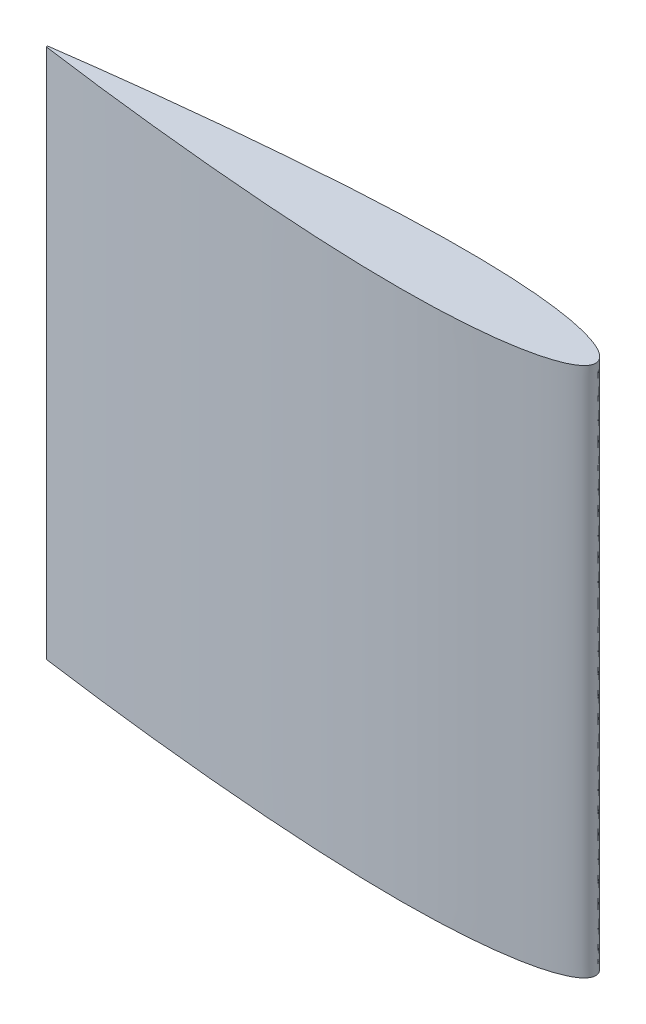
SolidWorks part; units mm, degrees
ref_plane "Front Plane" through (0, 0, 0) normal (0, 0, 1) x (1, 0, 0)
ref_plane "Top Plane" through (0, 0, 0) normal (0, 1, 0) x (1, 0, 0)
ref_plane "Right Plane" through (0, 0, 0) normal (1, 0, 0) x (0, 0, -1)
other "Center of Mass"
curve "Curve1"
  spline degree 3 poles (1, 0.0013, 0) (0.9998, 0.0013, 0) (0.999, 0.0014, 0) (0.9973, 0.0016, 0) (0.9944, 0.002, 0) (0.9903, 0.0026, 0) (0.9851, 0.0033, 0) (0.9788, 0.0042, 0) (0.9713, 0.0052, 0) (0.9627, 0.0064, 0) (0.9531, 0.0077, 0) (0.9424, 0.0091, 0) (0.9307, 0.0106, 0) (0.9179, 0.0122, 0) (0.9042, 0.014, 0) (0.8895, 0.0158, 0) (0.874, 0.0177, 0) (0.8575, 0.0196, 0) (0.8402, 0.0217, 0) (0.8222, 0.0237, 0) (0.8033, 0.0259, 0) (0.7838, 0.028, 0) (0.7636, 0.0302, 0) (0.7428, 0.0324, 0) (0.7214, 0.0345, 0) (0.6995, 0.0367, 0) (0.6772, 0.0388, 0) (0.6544, 0.0409, 0) (0.6313, 0.043, 0) (0.6078, 0.045, 0) (0.5841, 0.0469, 0) (0.5602, 0.0488, 0) (0.5362, 0.0505, 0) (0.5121, 0.0522, 0) (0.4879, 0.0537, 0) (0.4638, 0.0551, 0) (0.4398, 0.0563, 0) (0.4159, 0.0574, 0) (0.3922, 0.0583, 0) (0.3688, 0.0591, 0) (0.3456, 0.0596, 0) (0.3228, 0.0599, 0) (0.3005, 0.0601, 0) (0.2786, 0.06, 0) (0.2572, 0.0596, 0) (0.2364, 0.0591, 0) (0.2162, 0.0583, 0) (0.1966, 0.0572, 0) (0.1778, 0.056, 0) (0.1597, 0.0544, 0) (0.1425, 0.0527, 0) (0.126, 0.0507, 0) (0.1104, 0.0486, 0) (0.0958, 0.0462, 0) (0.0821, 0.0436, 0) (0.0693, 0.0408, 0) (0.0576, 0.0378, 0) (0.0468, 0.0347, 0) (0.0372, 0.0313, 0) (0.0286, 0.0279, 0) (0.0211, 0.0243, 0) (0.0147, 0.0206, 0) (0.0094, 0.0167, 0) (0.0053, 0.0128, 0) (0.0023, 0.0087, 0) (0.0004, 0.0044, 0) (-0.0002, 0, 0) (0.0004, -0.0044, 0) (0.0023, -0.0087, 0) (0.0053, -0.0128, 0) (0.0094, -0.0167, 0) (0.0147, -0.0206, 0) (0.0211, -0.0243, 0) (0.0286, -0.0279, 0) (0.0372, -0.0313, 0) (0.0468, -0.0347, 0) (0.0576, -0.0378, 0) (0.0693, -0.0408, 0) (0.0821, -0.0436, 0) (0.0958, -0.0462, 0) (0.1104, -0.0486, 0) (0.126, -0.0507, 0) (0.1425, -0.0527, 0) (0.1597, -0.0544, 0) (0.1778, -0.056, 0) (0.1966, -0.0572, 0) (0.2162, -0.0583, 0) (0.2364, -0.0591, 0) (0.2572, -0.0596, 0) (0.2786, -0.06, 0) (0.3005, -0.0601, 0) (0.3228, -0.0599, 0) (0.3456, -0.0596, 0) (0.3688, -0.0591, 0) (0.3922, -0.0583, 0) (0.4159, -0.0574, 0) (0.4398, -0.0563, 0) (0.4638, -0.0551, 0) (0.4879, -0.0537, 0) (0.5121, -0.0522, 0) (0.5362, -0.0505, 0) (0.5602, -0.0488, 0) (0.5841, -0.0469, 0) (0.6078, -0.045, 0) (0.6313, -0.043, 0) (0.6544, -0.0409, 0) (0.6772, -0.0388, 0) (0.6995, -0.0367, 0) (0.7214, -0.0345, 0) (0.7428, -0.0324, 0) (0.7636, -0.0302, 0) (0.7838, -0.028, 0) (0.8033, -0.0259, 0) (0.8222, -0.0237, 0) (0.8402, -0.0217, 0) (0.8575, -0.0196, 0) (0.874, -0.0177, 0) (0.8895, -0.0158, 0) (0.9042, -0.014, 0) (0.9179, -0.0122, 0) (0.9307, -0.0106, 0) (0.9424, -0.0091, 0) (0.9531, -0.0077, 0) (0.9627, -0.0064, 0) (0.9713, -0.0052, 0) (0.9788, -0.0042, 0) (0.9851, -0.0033, 0) (0.9903, -0.0026, 0) (0.9944, -0.002, 0) (0.9973, -0.0016, 0) (0.999, -0.0014, 0) (0.9998, -0.0013, 0) (1, -0.0013, 0) knots 0 0 0 0 0.000289 0.001156 0.002598 0.004612 0.007194 0.010336 0.014031 0.018272 0.023046 0.028343 0.03415 0.040454 0.047238 0.054489 0.062187 0.070314 0.078852 0.08778 0.097078 0.106722 0.116691 0.126961 0.137507 0.148306 0.159331 0.170556 0.181957 0.193504 0.205171 0.216932 0.228758 0.240621 0.252495 0.26435 0.276161 0.287898 0.299536 0.311047 0.322405 0.333584 0.344559 0.355306 0.3658 0.376018 0.385937 0.395538 0.404798 0.413699 0.422221 0.430349 0.438066 0.445357 0.452209 0.458612 0.464554 0.47003 0.475035 0.479569 0.483637 0.48725 0.490431 0.493219 0.495674 0.497891 0.5 0.502109 0.504326 0.506781 0.509569 0.51275 0.516363 0.520431 0.524965 0.52997 0.535446 0.541388 0.547791 0.554643 0.561934 0.569651 0.577779 0.586301 0.595202 0.604462 0.614063 0.623982 0.6342 0.644694 0.655441 0.666416 0.677595 0.688953 0.700464 0.712102 0.723839 0.73565 0.747505 0.759379 0.771242 0.783068 0.794829 0.806496 0.818043 0.829444 0.840669 0.851694 0.862493 0.873039 0.883309 0.893278 0.902922 0.91222 0.921148 0.929686 0.937813 0.945511 0.952762 0.959546 0.96585 0.971657 0.976954 0.981728 0.985969 0.989664 0.992806 0.995388 0.997402 0.998844 0.999711 1 1 1 1
sketch "Sketch3" plane through (0, 0, 0) normal (0, 1, 0) x (1, 0, 0)
  line L0 (-600, 0.811) -> (-600, 1.189)
  line L1 (-450, 1) -> (-600, 1) construction
  line L2 (-450, 1) -> (-450, -67.7487) construction
  spline S0 degree 3 poles (-600, 0.811) (-597.1383, 0.409) (-586.3551, -1.0487) (-571.3391, -2.8356) (-553.4048, -4.6847) (-539.8063, -5.8991) (-526.805, -6.8522) (-516.0279, -7.4788) (-505.4381, -7.8939) (-495.2572, -8.0517) (-486.6423, -7.9301) (-479.5995, -7.6106) (-474.0744, -7.2001) (-469.0237, -6.6516) (-465.1394, -6.0705) (-462.3078, -5.5341) (-460.3955, -5.1154) (-458.6338, -4.6692) (-457.0267, -4.1976) (-455.5775, -3.7022) (-454.2895, -3.1846) (-453.1652, -2.6464) (-452.2067, -2.0886) (-451.4151, -1.5123) (-450.792, -0.9164) (-450.3389, -0.2993) (-450.0619, 0.342) (-449.9698, 1) (-450.0619, 1.658) (-450.3389, 2.2993) (-450.792, 2.9164) (-451.4151, 3.5123) (-452.2067, 4.0886) (-453.1652, 4.6464) (-454.2895, 5.1846) (-455.5775, 5.7022) (-457.0267, 6.1976) (-458.6338, 6.6692) (-460.3955, 7.1154) (-463.0341, 7.6932) (-466.6909, 8.3286) (-471.4868, 8.9425) (-477.7882, 9.5143) (-485.6982, 9.9164) (-496.4309, 10.0682) (-507.8157, 9.8328) (-519.6106, 9.2909) (-530.4, 8.605) (-542.1964, 7.6892) (-552.5331, 6.7493) (-565.8552, 5.4137) (-579.0317, 3.9401) (-591.6106, 2.3422) (-597.8927, 1.484) (-599.7377, 1.2258) (-600, 1.189) knots 0 0 0 0 0.028343 0.106722 0.148306 0.205171 0.240621 0.276161 0.311047 0.344559 0.376018 0.395538 0.413699 0.430349 0.445357 0.452209 0.458612 0.464554 0.47003 0.475035 0.479569 0.483637 0.48725 0.490431 0.493219 0.495674 0.497891 0.5 0.502109 0.504326 0.506781 0.509569 0.51275 0.516363 0.520431 0.524965 0.52997 0.535446 0.541388 0.547791 0.561934 0.577779 0.595202 0.623982 0.655441 0.700464 0.73565 0.771242 0.806496 0.851694 0.873039 0.937813 0.981728 0.997402 1 1 1 1
  point P4 (-600, 1)
  dimension "D1" = 150
  dimension "D2" = 450
  dimension "D3" = 1
extrude "Boss-Extrude1" add sketch "Sketch3" along normal up to surface (145 mm away)
ref_plane "Plane1" through (0, 0, 0) normal (0, 0, 1) x (1, 0, 0)
sketch "Sketch4" plane through (0, 0, 0) normal (0, 0, 1) x (1, 0, 0)
  line L0 (-600, -0.1575) -> (-600, 0.1575)
  line L1 (-475, 0) -> (-600, 0) construction
  line L2 (-475, 0) -> (-475, -6.0209) construction
  line L3 (-450, 0) -> (-450, 145) construction
  line L4 (-450, 0) -> (-600, 0) construction
  spline S0 degree 3 poles (-600, -0.1575) (-597.6153, -0.4925) (-588.6292, -1.7072) (-576.1159, -3.1963) (-561.1707, -4.7372) (-549.8386, -5.7492) (-539.0042, -6.5435) (-530.0233, -7.0656) (-521.1984, -7.4116) (-512.7143, -7.543) (-505.5353, -7.4418) (-499.6663, -7.1755) (-495.062, -6.8334) (-490.8531, -6.3763) (-487.6162, -5.8921) (-485.2565, -5.4451) (-483.6629, -5.0962) (-482.1949, -4.7243) (-480.8556, -4.3313) (-479.6479, -3.9185) (-478.5746, -3.4872) (-477.6376, -3.0386) (-476.8389, -2.5738) (-476.1793, -2.0936) (-475.66, -1.597) (-475.2824, -1.0828) (-475.0516, -0.5483) (-474.9749, 0) (-475.0516, 0.5483) (-475.2824, 1.0828) (-475.66, 1.597) (-476.1793, 2.0936) (-476.8389, 2.5738) (-477.6376, 3.0386) (-478.5746, 3.4872) (-479.6479, 3.9185) (-480.8556, 4.3313) (-482.1949, 4.7243) (-483.6629, 5.0962) (-485.8617, 5.5776) (-488.9091, 6.1072) (-492.9057, 6.6187) (-498.1569, 7.0952) (-504.7485, 7.4303) (-513.6924, 7.5569) (-523.1797, 7.3607) (-533.0088, 6.9091) (-542, 6.3375) (-551.8303, 5.5743) (-560.4442, 4.7911) (-571.546, 3.6781) (-582.5264, 2.45) (-593.0088, 1.1185) (-598.2439, 0.4033) (-599.7814, 0.1882) (-600, 0.1575) knots 0 0 0 0 0.028343 0.106722 0.148306 0.205171 0.240621 0.276161 0.311047 0.344559 0.376018 0.395538 0.413699 0.430349 0.445357 0.452209 0.458612 0.464554 0.47003 0.475035 0.479569 0.483637 0.48725 0.490431 0.493219 0.495674 0.497891 0.5 0.502109 0.504326 0.506781 0.509569 0.51275 0.516363 0.520431 0.524965 0.52997 0.535446 0.541388 0.547791 0.561934 0.577779 0.595202 0.623982 0.655441 0.700464 0.73565 0.771242 0.806496 0.851694 0.873039 0.937813 0.981728 0.997402 1 1 1 1
  point P4 (-600, 0)
  point P11 (-600, 0)
  dimension "D1" = 125
  dimension "D2" = 25
ref_plane "Plane3" through (0, 0, 175) normal (0, 0, 1) x (1, 0, 0)
ref_plane "Plane4" through (0, 0, 20) normal (0, 0, 1) x (1, 0, 0)
